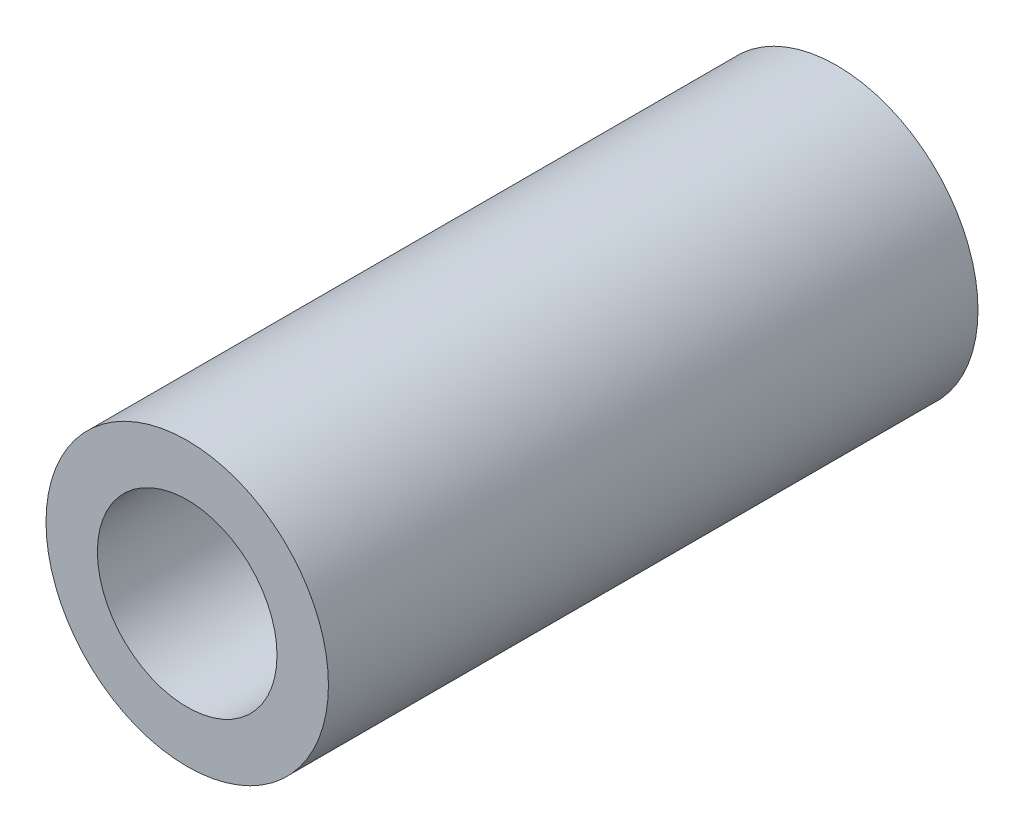
SolidWorks part; units mm, degrees
ref_plane "Front Plane" through (0, 0, 0) normal (0, 0, 1) x (1, 0, 0)
ref_plane "Top Plane" through (0, 0, 0) normal (0, 1, 0) x (1, 0, 0)
ref_plane "Right Plane" through (0, 0, 0) normal (1, 0, 0) x (0, 0, -1)
sketch "Sketch1" plane through (0, 0, 0) normal (0, 0, 1) x (1, 0, 0)
  circle A0 centre (0, 0) radius 25
  circle A1 centre (0, 0) radius 15.9
  dimension "D1" = 50
  dimension "D2" = 31.8
extrude "Boss-Extrude1" add sketch "Sketch1" along normal blind 115
